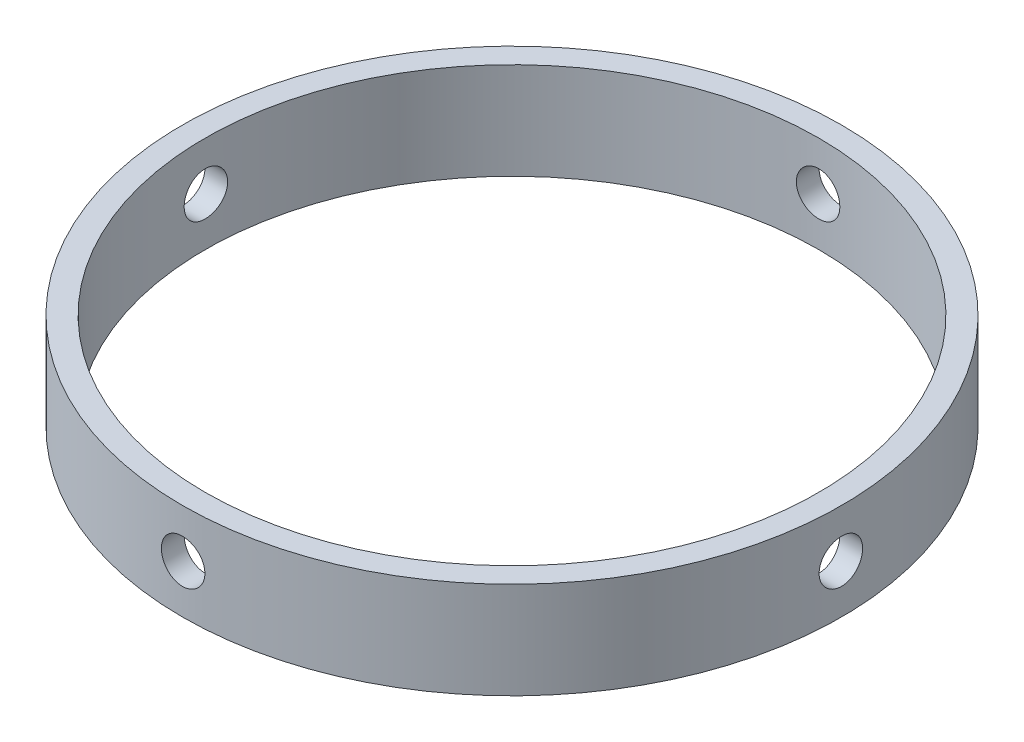
SolidWorks part; units mm, degrees
ref_plane "Front Plane" through (0, 0, 0) normal (0, 0, 1) x (1, 0, 0)
ref_plane "Top Plane" through (0, 0, 0) normal (0, 1, 0) x (1, 0, 0)
ref_plane "Right Plane" through (0, 0, 0) normal (1, 0, 0) x (0, 0, -1)
sketch "Sketch1" plane through (0, 0, 0) normal (0, 1, 0) x (1, 0, 0)
  circle A0 centre (0, 0) radius 31.75
  circle A1 centre (0, 0) radius 34.1
  dimension "D1" = 63.5
  dimension "D2" = 68.2
extrude "Boss-Extrude1" add sketch "Sketch1" along normal mid plane 10
ref_plane "Plane1" through (0, 0, -34.1) normal (0, 0, -1) x (-1, 0, 0)
sketch "Sketch2" plane through (0, 0, 0) normal (0, 0, 1) x (1, 0, 0)
  circle A0 centre (0, 0) radius 2.25
  dimension "D1" = 4.5
extrude "Cut-Extrude1" cut sketch "Sketch2" against normal through all
pattern_circular "CirPattern1" count 4 over 360 about axis through (0, 5, 0) along (0, -1, 0) of "Cut-Extrude1"
